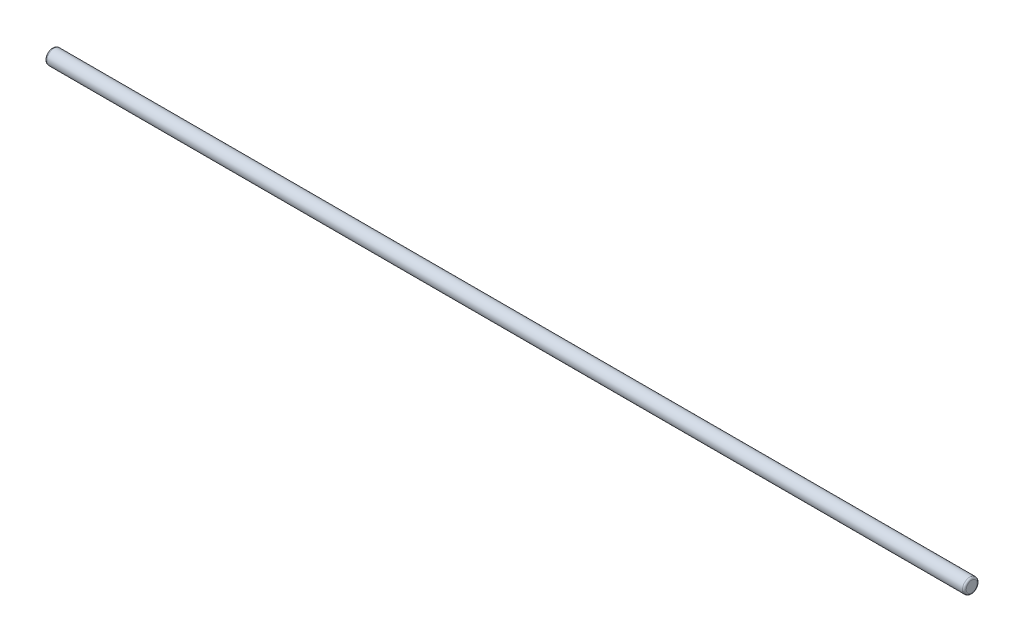
SolidWorks part; units mm, degrees
ref_plane "Front Plane" through (0, 0, 0) normal (0, 0, 1) x (1, 0, 0)
ref_plane "Top Plane" through (0, 0, 0) normal (0, 1, 0) x (1, 0, 0)
ref_plane "Right Plane" through (0, 0, 0) normal (1, 0, 0) x (0, 0, -1)
sketch "ProfileSketch1" plane through (0, 0, 0) normal (1, 0, 0) x (0, 0, -1)
  circle A0 centre (0, 0) radius 4
  dimension "D1" = 8
extrude "ProfileBoss-Extrude1" add sketch "ProfileSketch1" along normal blind 500
fillet "Fillet1" radius 1 2 edges at (0, 0, -4) (500, 0, -4)
equation "\"RodShaft8mmDiameter\"= 8mm"
equation "\"RodShaft500mmLength\"= 500mm"
equation "\"D1@ProfileBoss-Extrude1\" = \"RodShaft500mmLength\""
equation "\"D1@ProfileSketch1\"=\"RodShaft8mmDiameter\""
